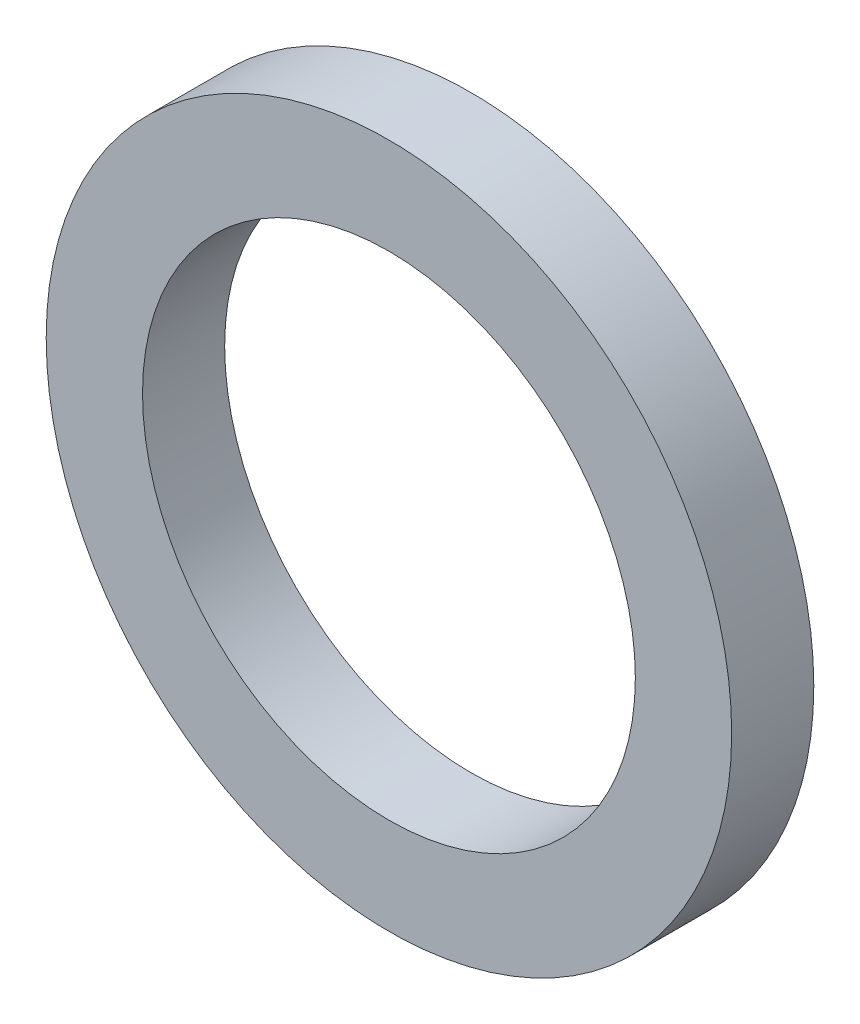
SolidWorks part; units mm, degrees
material "Nylon 101"
ref_plane "Front Plane" through (0, 0, 0) normal (0, 0, 1) x (1, 0, 0)
ref_plane "Top Plane" through (0, 0, 0) normal (0, 1, 0) x (1, 0, 0)
ref_plane "Right Plane" through (0, 0, 0) normal (1, 0, 0) x (0, 0, -1)
sketch "Sketch1" plane through (0, 0, 0) normal (0, 0, 1) x (1, 0, 0)
  circle A0 centre (0, 0) radius 6.6243
  circle A1 centre (0, 0) radius 4.7625
  dimension "D1" = 13.2486
  dimension "D2" = 9.525
extrude "Boss-Extrude1" add sketch "Sketch1" along normal mid plane 1.5875
